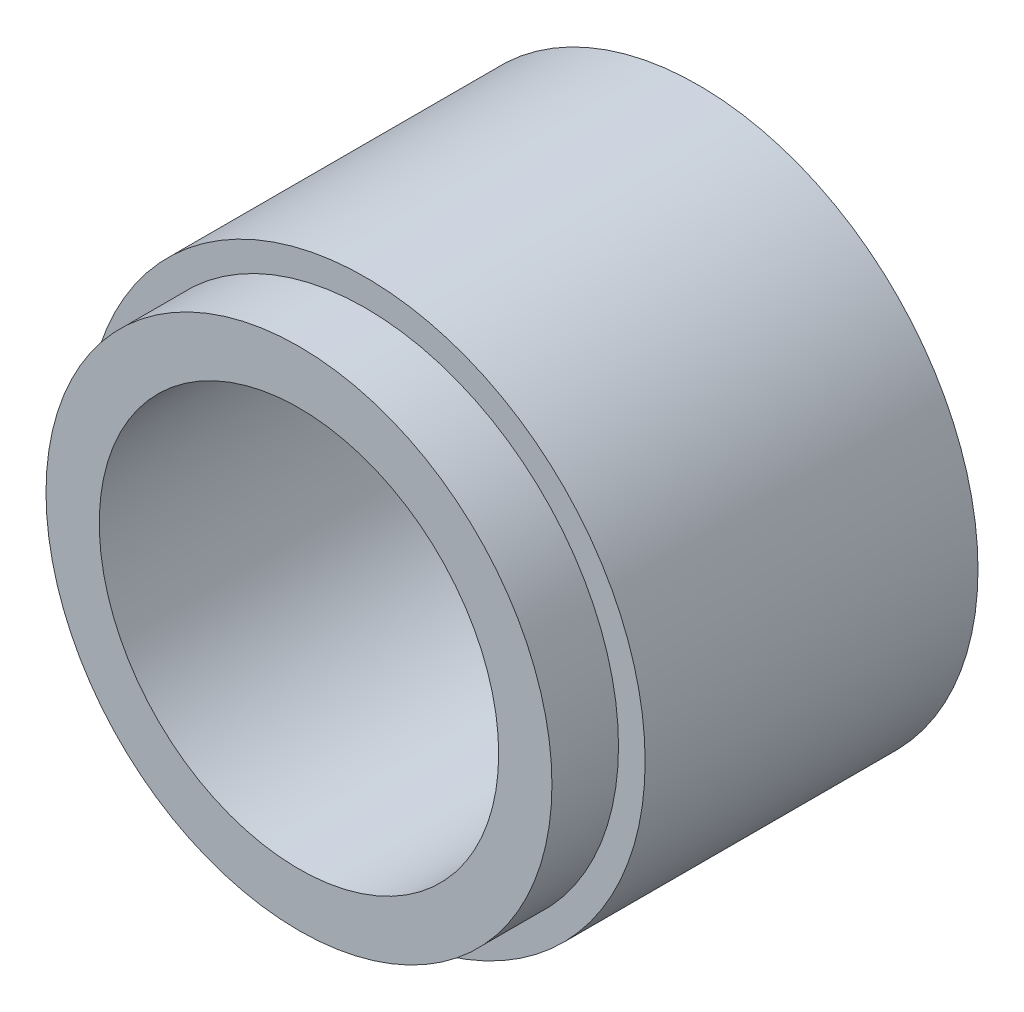
SolidWorks part; units mm, degrees
material "黄铜"
ref_plane "前视基准面" through (0, 0, 0) normal (0, 0, 1) x (1, 0, 0)
ref_plane "上视基准面" through (0, 0, 0) normal (0, 1, 0) x (1, 0, 0)
ref_plane "右视基准面" through (0, 0, 0) normal (1, 0, 0) x (0, 0, -1)
other "Configuration Table"
sketch "草图1" plane through (0, 0, 0) normal (0, 0, 1) x (1, 0, 0)
  circle A0 centre (0, 0) radius 1.5
  circle A1 centre (0, 0) radius 2.1
  dimension "D1" = 3
  dimension "D2" = 4.2
extrude "凸台-拉伸1" add sketch "草图1" along normal blind 3
sketch "草图2" plane through (0, 0, 3) normal (0, 0, 1) x (1, 0, 0)
  circle A0 centre (0, 0) radius 1.9
  circle A1 centre (0, 0) radius 2.1
  dimension "D1" = 4.2
  dimension "D2" = 3.8
extrude "切除-拉伸1" cut sketch "草图2" against normal blind 0.5
